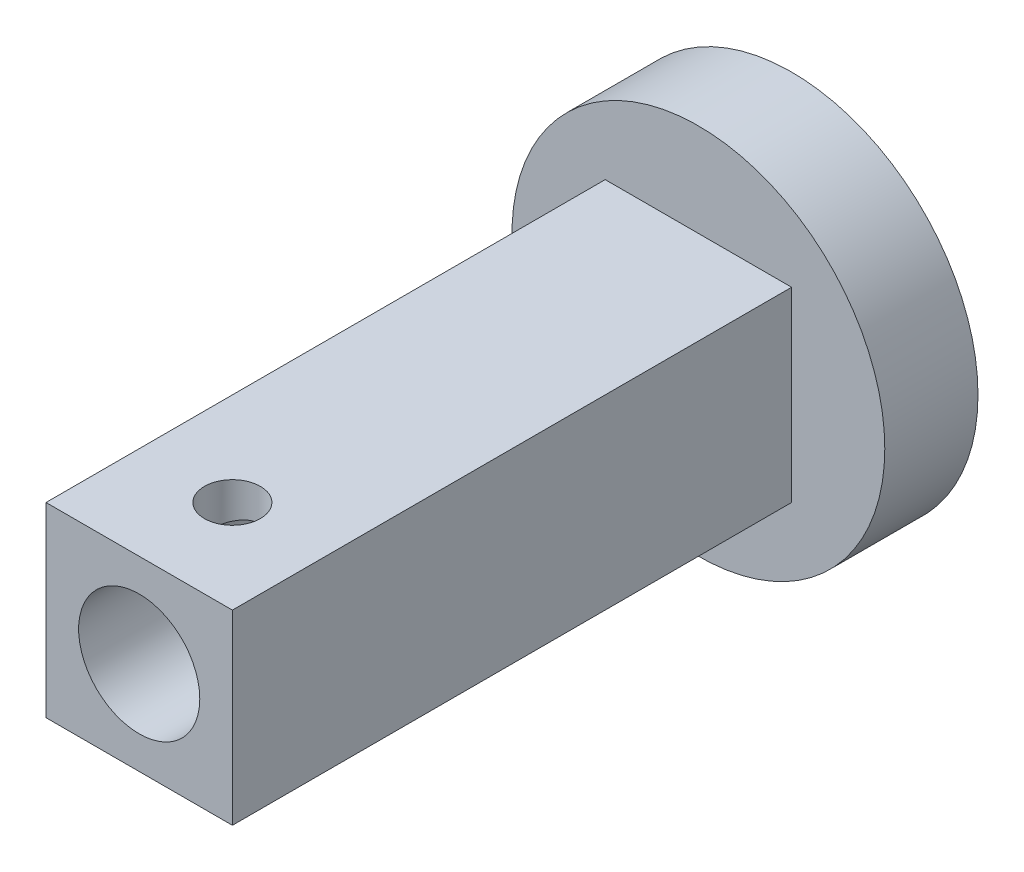
SolidWorks part; units mm, degrees
ref_plane "Спереди" through (0, 0, 0) normal (0, 0, 1) x (1, 0, 0)
ref_plane "Сверху" through (0, 0, 0) normal (0, 1, 0) x (1, 0, 0)
ref_plane "Справа" through (0, 0, 0) normal (1, 0, 0) x (0, 0, -1)
sketch "Эскиз1" plane through (0, 0, 0) normal (0, 0, 1) x (1, 0, 0)
  circle A0 centre (0, 0) radius 10
  circle A1 centre (0, 0) radius 3.25
  dimension "D1" = 20
  dimension "D2" = 6.5
extrude "Бобышка-Вытянуть1" add sketch "Эскиз1" along normal blind 5
sketch "Эскиз2" plane through (0, 0, 5) normal (0, 0, 1) x (1, 0, 0)
  line L1 (-5, -5) -> (5, -5)
  line L2 (-5, -5) -> (-5, 5)
  line L3 (-5, 5) -> (5, 5)
  line L4 (5, -5) -> (5, 5)
  line L5 (-5, -5) -> (5, 5) construction
  line L6 (-5, 5) -> (5, -5) construction
  circle A1 centre (0, 0) radius 3.25 construction
  point P0 (0, 0)
  dimension "D1" = 10
  dimension "D2" = 10
extrude "Бобышка-Вытянуть4" add sketch "Эскиз2" along normal blind 30
sketch "Эскиз5" plane through (0, 0, 35) normal (0, 0, 1) x (1, 0, 0)
sketch "Эскиз6" plane through (0, 0, 35) normal (0, 0, 1) x (1, 0, 0)
  circle A0 centre (0, 0) radius 3.25
  dimension "D1" = 6.5
extrude "Вырез-Вытянуть1" cut sketch "Эскиз6" against normal blind 30
sketch "Эскиз7" plane through (0, 5, 0) normal (0, 1, 0) x (1, 0, 0)
  line L0 (5, -35) -> (-5, -35) construction
  circle A0 centre (0, -30) radius 1.5
  dimension "D1" = 3
  dimension "D2" = 5
extrude "Вырез-Вытянуть3" cut sketch "Эскиз7" against normal blind 5
